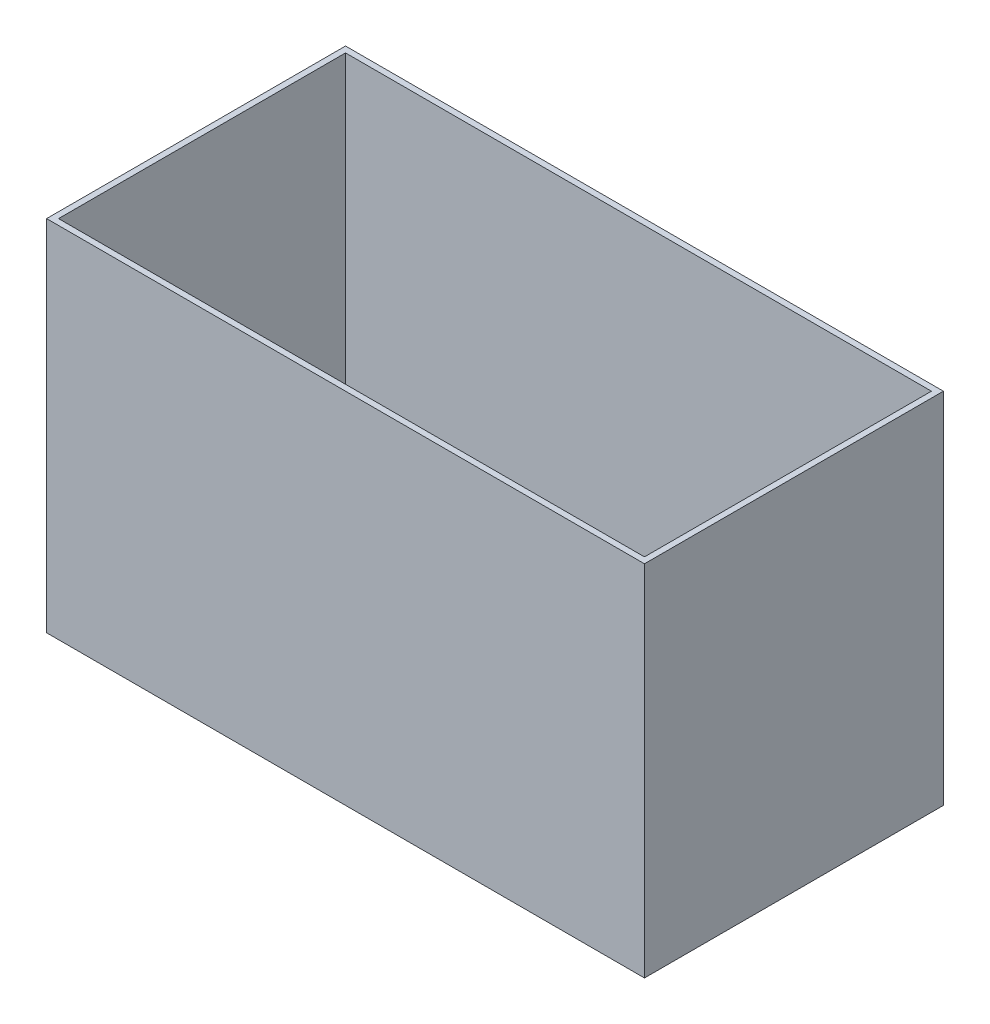
SolidWorks part; units mm, degrees
ref_plane "Front Plane" through (0, 0, 0) normal (0, 0, 1) x (1, 0, 0)
ref_plane "Top Plane" through (0, 0, 0) normal (0, 1, 0) x (1, 0, 0)
ref_plane "Right Plane" through (0, 0, 0) normal (1, 0, 0) x (0, 0, -1)
sketch "Sketch1" plane through (0, 0, 0) normal (0, 1, 0) x (1, 0, 0)
  line L1 (0, 0) -> (500, 0)
  line L2 (0, 0) -> (0, 250)
  line L3 (0, 250) -> (500, 250)
  line L4 (500, 0) -> (500, 250)
  dimension "D1" = 250
  dimension "D2" = 500
extrude "Boss-Extrude1" add sketch "Sketch1" along normal blind 300
shell "Shell1" thickness 5
